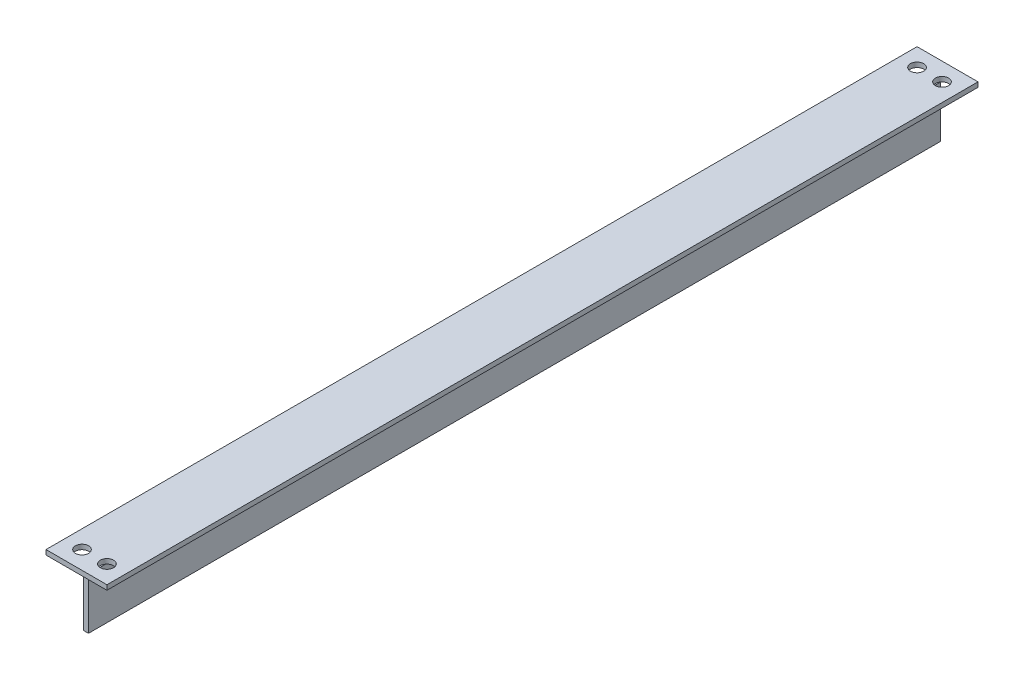
SolidWorks part; units mm, degrees
material "5052-H32"
ref_plane "Plano frontal" through (0, 0, 0) normal (0, 0, 1) x (1, 0, 0)
ref_plane "Plano superior" through (0, 0, 0) normal (0, 1, 0) x (1, 0, 0)
ref_plane "Plano direito" through (0, 0, 0) normal (1, 0, 0) x (0, 0, -1)
sketch "Esboço1" plane through (0, 0, 0) normal (0, 0, 1) x (1, 0, 0)
  line L0 (-12.7, 0) -> (12.7, 0)
  line L1 (-1, -2) -> (-1, -25.4)
  line L2 (-1, -25.4) -> (1, -25.4)
  line L4 (1, -2) -> (12.7, -2)
  line L6 (-1, -2) -> (-12.7, -2)
  line L7 (-12.7, -2) -> (-12.7, 0)
  line L8 (0, -29.2972) -> (0, 2.6822) construction
  line L9 (1, -2) -> (1, -25.4)
  line L10 (12.7, -2) -> (12.7, 0)
  dimension "D1" = 25.4
  dimension "D2" = 2
  dimension "D3" = 25.4
extrude "Ressalto-extrusão1" add sketch "Esboço1" along normal mid plane 363
sketch "Esboço3" plane through (0, 0, 0) normal (1, 0, 0) x (0, 0, -1)
  line L0 (-177.5, -4) -> (-168, -4)
  line L1 (-181.5, -25.4) -> (-181.5, -2) construction
  line L2 (-168, -4) -> (-168, -2)
  line L3 (-181.5, -2) -> (181.5, -2) construction
  line L4 (-168, -2) -> (-181.5, -2)
  line L5 (-181.5, -2) -> (-181.5, -25.4)
  line L6 (-181.5, -2) -> (181.5, -2) construction
  line L7 (0, 18.294) -> (0, -38.1067) construction
  line L12 (-177.5, -4) -> (-177.5, -25.4)
  line L13 (-181.5, -25.4) -> (181.5, -25.4) construction
  line L14 (-181.5, -25.4) -> (-177.5, -25.4)
  line L27 (181.5, -25.4) -> (177.5, -25.4)
  line L28 (177.5, -4) -> (177.5, -25.4)
  line L29 (181.5, -2) -> (181.5, -25.4)
  line L30 (168, -2) -> (181.5, -2)
  line L31 (168, -4) -> (168, -2)
  line L32 (177.5, -4) -> (168, -4)
  dimension "D1" = 2
  dimension "D2" = 13.5
  dimension "D3" = 4
extrude "Corte-extrusão2" cut sketch "Esboço3" against normal mid plane 100
hole_wizard "Furo de diâmetro Ø5.5 (5.5)1" positions "Esboço4" profile "Esboço5" hole size "Ø5.5" standard "DIN" end condition through all
sketch "Esboço4" plane through (0, 0, 0) normal (0, 1, 0) x (1, 0, 0)
  line L0 (0, 185.1973) -> (0, -185.1973) construction
  line L2 (-65.8783, 0) -> (65.8783, 0) construction
  line L4 (12.7, -181.5) -> (12.7, 181.5) construction
  line L5 (12.7, -181.5) -> (-12.7, -181.5) construction
  point P0 (5.2, -174)
  point P12 (0, -185.1973)
  point P13 (-5.2, -174)
  point P14 (-5.2, 174)
  point P15 (5.2, 174)
  dimension "D1" = 7.5
  dimension "D2" = 7.5
sketch "Esboço5" plane through (5.2, 0, 174) normal (1, 0, 0) x (0, 0, 1)
  line L0 (0, 0) -> (0, 25.4)
  line L1 (0, 25.4) -> (2.75, 25.4)
  line L2 (2.75, 25.4) -> (2.75, 0)
  line L5 (2.75, 0) -> (0, 0)
  line L11 (0, -6.35) -> (0, 107.95) construction
  dimension "Thru Hole Dia." = 5.5
  dimension "Thru Hole Depth" = 25.4
